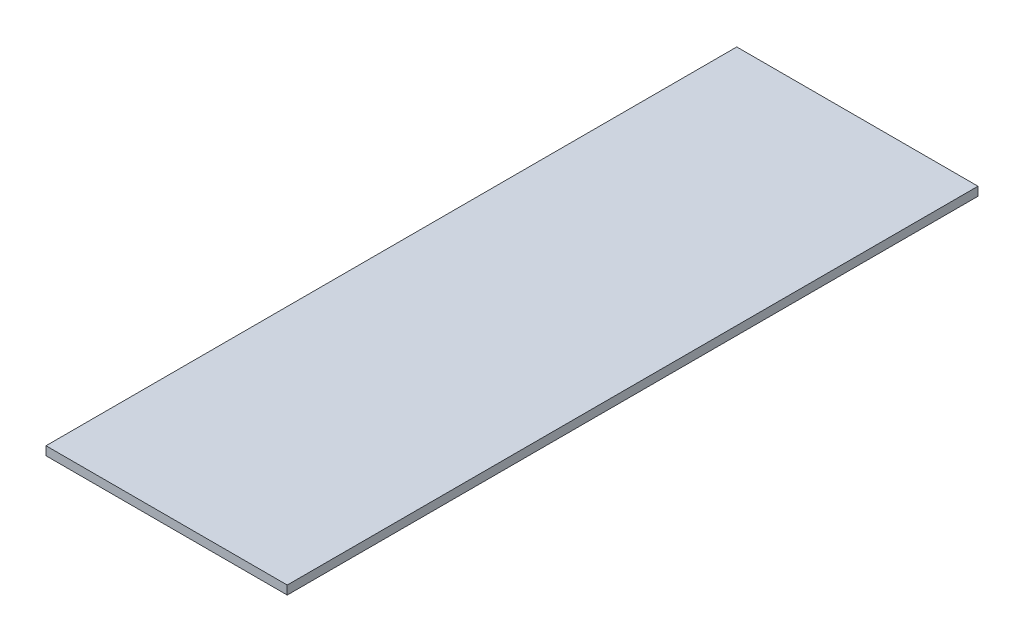
SolidWorks part; units mm, degrees
ref_plane "Front Plane" through (0, 0, 0) normal (0, 0, 1) x (1, 0, 0)
ref_plane "Top Plane" through (0, 0, 0) normal (0, 1, 0) x (1, 0, 0)
ref_plane "Right Plane" through (0, 0, 0) normal (1, 0, 0) x (0, 0, -1)
sketch "Esquisse1" plane through (0, 0, 0) normal (0, 0, 1) x (1, 0, 0)
  line L0 (-20.1279, -5.86) -> (21.0827, -5.86)
  line L1 (-20.1279, -5.86) -> (-20.1279, -7.3468)
  line L2 (-20.1279, -7.3468) -> (21.0827, -7.3468)
  line L3 (21.0827, -5.86) -> (21.0827, -7.3468)
extrude "Boss.-Extru.1" add sketch "Esquisse1" along normal blind 118
